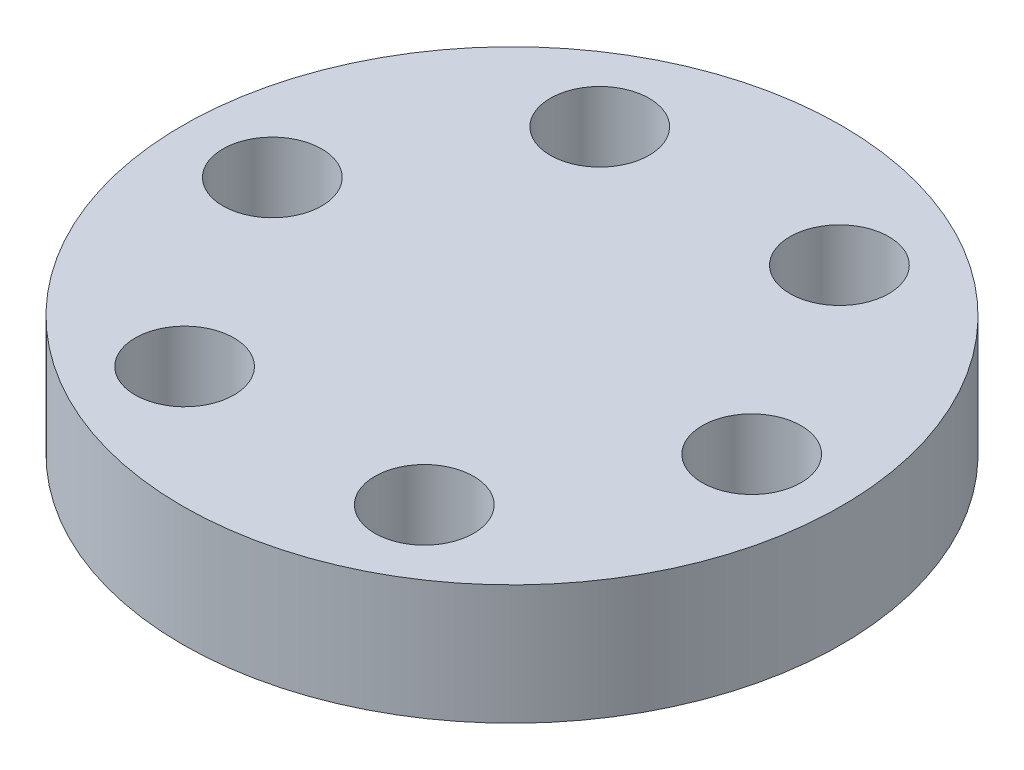
SolidWorks part; units mm, degrees
ref_plane "Front Plane" through (0, 0, 0) normal (0, 0, 1) x (1, 0, 0)
ref_plane "Top Plane" through (0, 0, 0) normal (0, 1, 0) x (1, 0, 0)
ref_plane "Right Plane" through (0, 0, 0) normal (1, 0, 0) x (0, 0, -1)
sketch "Sketch1" plane through (0, 0, 0) normal (0, 1, 0) x (1, 0, 0)
  circle A0 centre (0, 0) radius 11
  circle A1 centre (-4, 6.9282) radius 1.65
  circle A2 centre (4, 6.9282) radius 1.65
  circle A3 centre (8, 0) radius 1.65
  circle A4 centre (4, -6.9282) radius 1.65
  circle A5 centre (-4, -6.9282) radius 1.65
  circle A6 centre (-8, 0) radius 1.65
  dimension "D3" = 3.3
  dimension "D4" = 22
  dimension "D2" = 16
  dimension "D1" = 6
extrude "Boss-Extrude1" add sketch "Sketch1" along normal blind 4
